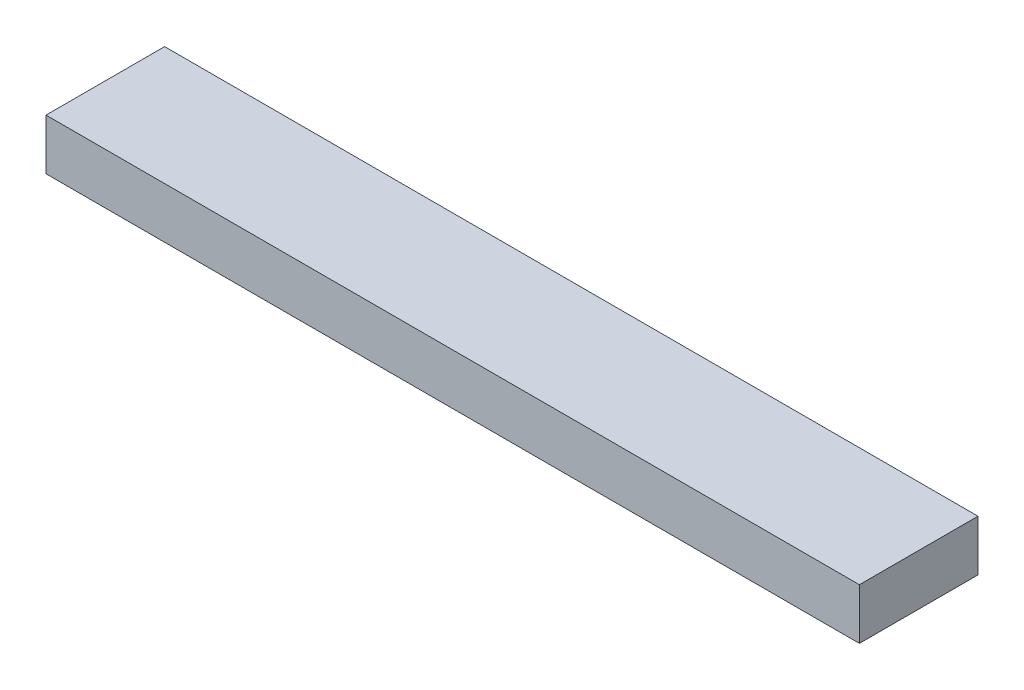
SolidWorks part; units mm, degrees
ref_plane "Front Plane" through (0, 0, 0) normal (0, 0, 1) x (1, 0, 0)
ref_plane "Top Plane" through (0, 0, 0) normal (0, 1, 0) x (1, 0, 0)
ref_plane "Right Plane" through (0, 0, 0) normal (1, 0, 0) x (0, 0, -1)
sketch "Sketch1" plane through (0, 0, 0) normal (1, 0, 0) x (0, -1, 0)
  line L1 (-19.05, -44.45) -> (19.05, -44.45)
  line L2 (-19.05, -44.45) -> (-19.05, 44.45)
  line L3 (-19.05, 44.45) -> (19.05, 44.45)
  line L4 (19.05, -44.45) -> (19.05, 44.45)
  line L5 (-19.05, -44.45) -> (19.05, 44.45) construction
  line L6 (-19.05, 44.45) -> (19.05, -44.45) construction
  point P0 (0, 0)
  dimension "D1" = 38.1
  dimension "D2" = 88.9
extrude "Boss-Extrude1" add sketch "Sketch1" along normal blind 609.6
